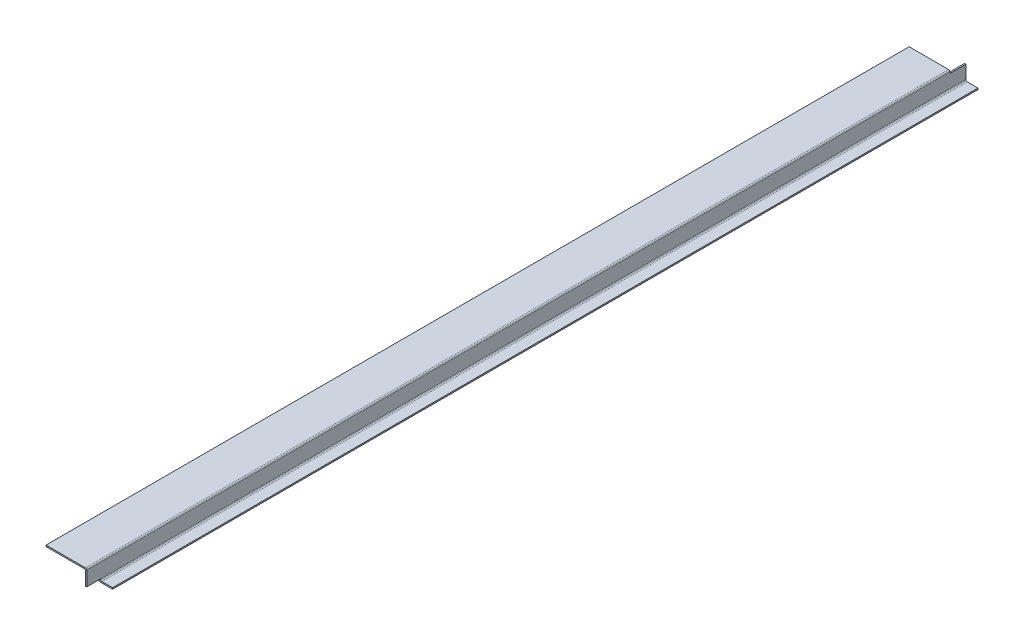
SolidWorks part; units mm, degrees
ref_plane "Front Plane" through (0, 0, 0) normal (0, 0, 1) x (1, 0, 0)
ref_plane "Top Plane" through (0, 0, 0) normal (0, 1, 0) x (1, 0, 0)
ref_plane "Right Plane" through (0, 0, 0) normal (1, 0, 0) x (0, 0, -1)
sketch "Sketch1" plane through (0, 0, 0) normal (0, 0, 1) x (1, 0, 0)
  line L0 (0, 0) -> (87, 0)
  line L1 (87, 0) -> (87, -38)
  line L2 (87, -38) -> (117, -38)
  line L3 (0, 3) -> (90, 3)
  line L4 (90, 3) -> (90, -35)
  line L5 (90, -35) -> (117, -35)
  line L6 (0, 3) -> (0, 0)
  line L7 (117, -35) -> (117, -38)
  dimension "D1" = 3
  dimension "D2" = 90
  dimension "D3" = 27
  dimension "D4" = 38
extrude "Boss-Extrude1" add sketch "Sketch1" along normal blind 1940
fillet "Fillet1" radius 3 4 edges at (87, -38, 970) (87, 0, 970) (90, -35, 970) (90, 3, 970)
sketch "Sketch2" plane through (0, 3, 0) normal (0, 1, 0) x (1, 0, 0)
  line L0 (0, 0) -> (0, -35)
  line L1 (0, -1940) -> (0, 0) construction
  line L2 (0, -35) -> (90, -35)
  line L3 (90, -1940) -> (90, 0) construction
  line L4 (90, -35) -> (90, 0)
  line L5 (90, 0) -> (0, 0)
  line L6 (87, -1940) -> (0, -1940) construction
  dimension "D1" = 1905
extrude "Cut-Extrude1" cut sketch "Sketch2" against normal blind 6
sketch "Sketch3" plane through (0, -38, 0) normal (0, -1, 0) x (1, 0, 0)
  line L7 (117, 1940) -> (117, 1910)
  line L8 (117, 1940) -> (117, 0) construction
  line L9 (117, 1910) -> (87, 1910)
  line L10 (87, 1940) -> (87, 35) construction
  line L11 (87, 1910) -> (87, 1940)
  line L12 (87, 1940) -> (117, 1940)
  dimension "D1" = 30
extrude "Cut-Extrude2" cut sketch "Sketch3" against normal blind 6
equation "\"D1@Boss-Extrude1\"=\"indoorHeight\""
equation "\"D1@Sketch2\"= \"indoorHeight\" + \"indoorHeight_para\" - 90 + 30"
equation "\"CarBeamWidth\"=700.0"
equation "\"WheelWidth\"=650.0"
equation "\"Wheel_FrontBoxDistance\"=1390.0"
equation "\"MetalSheet_3mm_length\"=5030.0"
equation "\"MetalSheet_3mm_width\"=1923.0"
equation "\"MetalSheet_3mm_FloorCut_L_length\"=1764.0"
equation "\"MetalSheet_3mm_FloorCut_L_disdance\"=1665.0"
equation "\"MetalSheet_3mm_FloorCut_R_length\"=1764.0"
equation "\"MetalSheet_3mm_FloorCut_R_disdance\"=1665.0"
equation "\"indoorHeight\"=1940.0"
equation "\"haveDoor_R\"=1"
equation "\"side_door_bottom_R_3mm_length\"=1934.0"
equation "\"1Bar_Side_RF_3mm_length\"=1493.0"
equation "\"1Bar_Side_RB_3mm_length\"=1493.0"
equation "\"DoorSeparator_RF_3mm_withHinge_toFrontDistance\"=1673.0"
equation "\"DoorSeparator_RF_3mm_withHinge_exist\"=1"
equation "\"DoorSeparator_RB_3mm_withHinge_toFrontDistance\"=3427.0"
equation "\"DoorSeparator_RB_3mm_withHinge_exist\"=1"
equation "\"Door_R1_L_open_Single_toFrontDistance\"=2547.5"
equation "\"Door_R1_L_open_Single_exist\"=1"
equation "\"Door_R1_R_open_Single_toFrontDistance\"=3422.0"
equation "\"Door_R1_R_open_Single_exist\"=1"
equation "\"x\"=66.0"
equation "\"da\"=62.0"
equation "\"SquareTube_length\"=1923.0"
equation "\"channelSteel_length\"=5030.0"
equation "\"SquareTube_inFront_AvgDistance\"=285.0"
equation "\"SquareTube_inFront_TotalCount\"=5"
equation "\"SquareTube_inFront1_cutDepth50_R\"=0.5"
equation "\"SquareTube_inFront1_cutDepth50_L\"=0.5"
equation "\"SquareTube_inFront2_cutDepth50_R\"=0.5"
equation "\"SquareTube_inFront2_cutDepth50_L\"=0.5"
equation "\"SquareTube_inFront3_cutDepth50_R\"=0.5"
equation "\"SquareTube_inFront3_cutDepth50_L\"=0.5"
equation "\"SquareTube_inFront4_cutDepth50_R\"=0.5"
equation "\"SquareTube_inFront4_cutDepth50_L\"=0.5"
equation "\"SquareTube_inFront5_cutDepth50_R\"=50"
equation "\"SquareTube_inFront5_cutDepth50_L\"=50"
equation "\"SquareTube_inFront6_cutDepth50_R\"=50"
equation "\"SquareTube_inFront6_cutDepth50_L\"=50"
equation "\"SquareTube_inFront7_cutDepth50_R\"=50"
equation "\"SquareTube_inFront7_cutDepth50_L\"=50"
equation "\"SquareTube_inFront8_cutDepth50_R\"=50"
equation "\"SquareTube_inFront8_cutDepth50_L\"=50"
equation "\"SquareTube_inFront9_cutDepth50_R\"=50"
equation "\"SquareTube_inFront9_cutDepth50_L\"=50"
equation "\"SquareTube_inFront10_cutDepth50_R\"=50"
equation "\"SquareTube_inFront10_cutDepth50_L\"=50"
equation "\"SquareTube_inFront11_cutDepth50_R\"=50"
equation "\"SquareTube_inFront11_cutDepth50_L\"=50"
equation "\"SquareTube_inFront12_cutDepth50_R\"=50"
equation "\"SquareTube_inFront12_cutDepth50_L\"=50"
equation "\"SquareTube_inFront13_cutDepth50_R\"=50"
equation "\"SquareTube_inFront13_cutDepth50_L\"=50"
equation "\"SquareTube_inFront14_cutDepth50_R\"=50"
equation "\"SquareTube_inFront14_cutDepth50_L\"=50"
equation "\"SquareTube_inBack_AvgDistance\"=333.125"
equation "\"SquareTube_inBack_TotalCount\"=9"
equation "\"SquareTube_inBack1_cutDepth50_R\"=50"
equation "\"SquareTube_inBack1_cutDepth50_L\"=50"
equation "\"SquareTube_inBack2_cutDepth50_R\"=50"
equation "\"SquareTube_inBack2_cutDepth50_L\"=50"
equation "\"SquareTube_inBack3_cutDepth50_R\"=50"
equation "\"SquareTube_inBack3_cutDepth50_L\"=50"
equation "\"SquareTube_inBack4_cutDepth50_R\"=50"
equation "\"SquareTube_inBack4_cutDepth50_L\"=50"
equation "\"SquareTube_inBack5_cutDepth50_R\"=50"
equation "\"SquareTube_inBack5_cutDepth50_L\"=50"
equation "\"SquareTube_inBack6_cutDepth50_R\"=0.5"
equation "\"SquareTube_inBack6_cutDepth50_L\"=0.5"
equation "\"SquareTube_inBack7_cutDepth50_R\"=0.5"
equation "\"SquareTube_inBack7_cutDepth50_L\"=0.5"
equation "\"SquareTube_inBack8_cutDepth50_R\"=0.5"
equation "\"SquareTube_inBack8_cutDepth50_L\"=0.5"
equation "\"indoorHeight_para\"=25.0"
